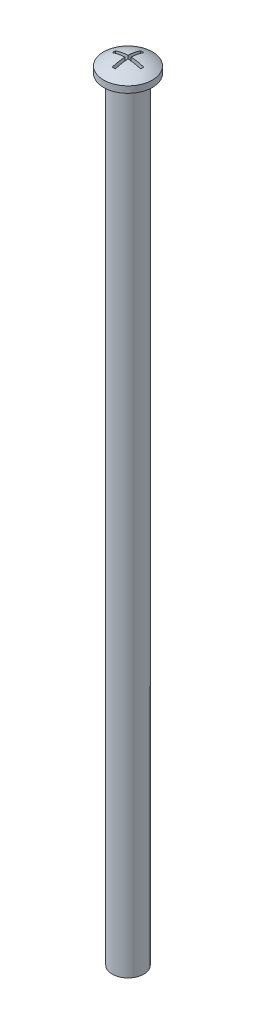
SolidWorks part; units mm, degrees
ref_plane "前视基准面" through (0, 0, 0) normal (0, 0, 1) x (1, 0, 0)
ref_plane "上视基准面" through (0, 0, 0) normal (0, 1, 0) x (1, 0, 0)
ref_plane "右视基准面" through (0, 0, 0) normal (1, 0, 0) x (0, 0, -1)
other "Configuration Table"
sketch "草图5" plane through (0, 0, 0) normal (0, 0, 1) x (1, 0, 0)
  line L0 (0, 0) -> (0, 2659.4822) construction
  line L1 (0, -14) -> (-1, -14)
  line L2 (-1, -14) -> (-1, 35)
  line L3 (-1, 35) -> (-1.55, 35)
  line L4 (-1.55, 35) -> (-1.55, 35.4115)
  line L5 (0, -14) -> (0, 35.8974)
  line L6 (-10.7814, -14) -> (1.5453, -14) construction
  spline S0 degree 2 poles (-1.55, 35.4115) (-0.8608, 35.896) (0, 35.8974) knots 0 0 0 1 1 1
  point P9 (0, 0)
  point P10 (0, 0)
  point P11 (0, -14)
  dimension "D1" = 2
  dimension "D2" = 3.1
revolve "旋转1" add sketch "草图5" angle 360 about L0
cosmetic thread "装饰螺纹线4"
ref_plane "基准面4" through (0, 35.4115, 0) normal (0, -1, 0) x (-1, 0, 0)
sketch "草图6" plane through (0, 35.4115, 0) normal (0, -1, 0) x (-1, 0, 0)
  line L0 (0.1, -0.1) -> (0.9, -0.1)
  line L1 (0.1, -0.9) -> (-0.1, -0.9)
  line L2 (0.1, -0.9) -> (0.1, -0.1)
  line L3 (0.1, 0.9) -> (-0.1, 0.9)
  line L4 (-0.1, -0.9) -> (-0.1, -0.1)
  line L5 (0.1, -0.9) -> (-0.1, 0.9) construction
  line L6 (0.1, 0.9) -> (-0.1, -0.9) construction
  line L7 (-0.9, -0.1) -> (-0.1, -0.1)
  line L8 (-0.9, -0.1) -> (-0.9, 0.1)
  line L9 (-0.9, 0.1) -> (-0.1, 0.1)
  line L10 (0.9, -0.1) -> (0.9, 0.1)
  line L11 (-0.9, -0.1) -> (0.9, 0.1) construction
  line L12 (-0.9, 0.1) -> (0.9, -0.1) construction
  line L13 (0.1, 0.1) -> (0.1, 0.9)
  line L14 (-0.1, 0.1) -> (-0.1, 0.9)
  line L15 (0.1, 0.1) -> (0.9, 0.1)
  point P0 (0, 0)
  point P6 (0, 0)
  dimension "D1" = 1.8
  dimension "D2" = 0.2
extrude "切除-拉伸2" cut sketch "草图6" against normal blind 10
